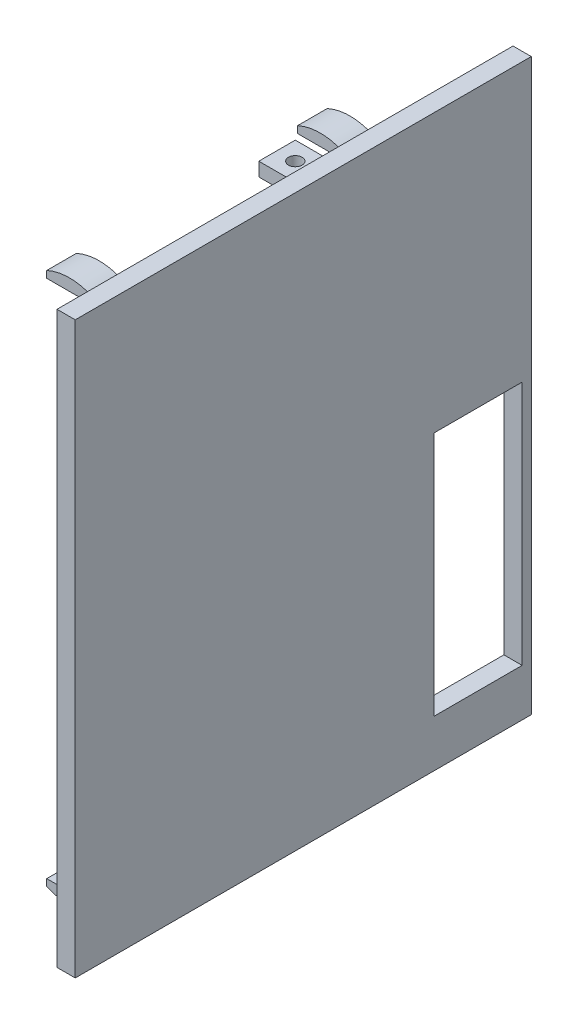
SolidWorks part; units mm, degrees
ref_plane "Front Plane" through (0, 0, 0) normal (0, 0, 1) x (1, 0, 0)
ref_plane "Top Plane" through (0, 0, 0) normal (0, 1, 0) x (1, 0, 0)
ref_plane "Right Plane" through (0, 0, 0) normal (1, 0, 0) x (0, 0, -1)
sketch "Sketch2" plane through (0, 0, 0) normal (0, 0, 1) x (1, 0, 0)
  line L1 (74.8705, 8.9597) -> (70.8705, 8.9597)
  line L2 (74.8705, 8.9597) -> (74.8705, -116.0403)
  line L3 (74.8705, -116.0403) -> (70.8705, -116.0403)
  line L4 (70.8705, 8.9597) -> (70.8705, -116.0403)
  dimension "D1" = 4
  dimension "D2" = 125
extrude "Boss-Extrude2" add sketch "Sketch2" along normal blind 100
sketch "Sketch6" plane through (70.8705, -52.3407, -13.6515) normal (-1, 0, 0) x (0, 1, 0)
  line L0 (61.3004, -13.6515) -> (-63.6996, -13.6515) construction
  line L1 (0.4704, -34.9991) -> (-53.3296, -34.9991)
  line L2 (0.4704, -34.9991) -> (0.4704, -15.6515)
  line L3 (0.4704, -15.6515) -> (-53.3296, -15.6515)
  line L4 (-53.3296, -34.9991) -> (-53.3296, -15.6515)
  line L6 (-63.6996, -113.6515) -> (-63.6996, -13.6515) construction
  dimension "D1" = 2
  dimension "D2" = 53.8
  dimension "D3" = 10.37
extrude "Cut-Extrude1" cut sketch "Sketch6" against normal up to next
sketch "Sketch7" plane through (74.8705, 0, 0) normal (1, 0, 0) x (0, 0, -1)
  line L0 (0, -116.0403) -> (0, 8.9597) construction
  line L1 (-50, -19.607) -> (-51.5, -19.607)
  line L2 (-50, -19.607) -> (-50, -39.607)
  line L3 (-50, -39.607) -> (-51.5, -39.607)
  line L4 (-51.5, -19.607) -> (-51.5, -39.607)
  dimension "D1" = 50
  dimension "D2" = 20
  dimension "D3" = 1.5
extrude "Boss-Extrude3" [suppressed] add sketch "Sketch7" against normal blind 16.5
pattern_linear "LPattern1" [suppressed] count 2 spacing 25
sketch "Sketch9" plane through (70.8705, 0, 0) normal (-1, 0, 0) x (0, 0, 1)
  line L0 (100, -116.0403) -> (0, -116.0403) construction
  line L1 (83.25, -110.5403) -> (89.75, -110.5403)
  line L2 (83.25, -110.5403) -> (83.25, -112.0403)
  line L3 (83.25, -112.0403) -> (89.75, -112.0403)
  line L4 (89.75, -110.5403) -> (89.75, -112.0403)
  line L5 (100, 8.9597) -> (100, -116.0403) construction
  dimension "D1" = 4
  dimension "D2" = 10.25
  dimension "D3" = 6.5
  dimension "D4" = 1.5
extrude "Boss-Extrude4" add sketch "Sketch9" along normal blind 12.5
sketch "Sketch10" plane through (0, 0, 89.75) normal (0, 0, 1) x (1, 0, 0)
  line L0 (58.3705, -112.0403) -> (70.8705, -112.0403) construction
  line L1 (58.3705, -112.0403) -> (68.3705, -112.0403)
  arc A0 (68.3705, -112.0403) -> (58.3705, -112.0403) centre (63.3705, -101.1316) cw
  dimension "D2" = 12
  dimension "D1" = 10
extrude "Boss-Extrude5" add sketch "Sketch10" against normal up to surface (6.5 mm away) up to face at (64.6205, -111.2903, 83.25)
pattern_linear "LPattern2" count 2 spacing 55 along (0, 0, -1) of "Boss-Extrude4", "Boss-Extrude5"
ref_plane "Plane2" through (0, -53.5403, 0) normal (0, 1, 0) x (1, 0, 0)
mirror "Mirror1" about plane through (0, -53.5403, 0) normal (0, 1, 0) of "LPattern2", "Boss-Extrude4", "Boss-Extrude5"
sketch "Sketch11" plane through (70.8705, 0, 0) normal (-1, 0, 0) x (0, 0, 1)
  line L0 (100, 8.9597) -> (100, -116.0403) construction
  line L1 (37.75, -109.0403) -> (45.75, -109.0403)
  line L2 (37.75, -109.0403) -> (37.75, -112.0403)
  line L3 (37.75, -112.0403) -> (45.75, -112.0403)
  line L4 (45.75, -109.0403) -> (45.75, -112.0403)
  line L5 (37.75, -109.0403) -> (45.75, -112.0403) construction
  line L6 (37.75, -112.0403) -> (45.75, -109.0403) construction
  line L7 (100, -116.0403) -> (0, -116.0403) construction
  point P0 (41.75, -110.5403)
  point P7 (37.75, -110.5403)
  dimension "D1" = 58.25
  dimension "D2" = 8
  dimension "D3" = 3
  dimension "D4" = 4
extrude "Boss-Extrude6" add sketch "Sketch11" along normal blind 10
sketch "Sketch12" plane through (0, -112.0403, 0) normal (0, -1, 0) x (-1, 0, 0)
  line L1 (-60.8705, -37.75) -> (-70.8705, -37.75) construction
  line L3 (-70.8705, -37.75) -> (-70.8705, -45.75) construction
  circle A0 centre (-64.8705, -41.75) radius 1.5
  point P4 (0, 0)
  point P6 (-70.8705, -43.0105)
  dimension "D1" = 3
  dimension "D2" = 4
  dimension "D3" = 6
extrude "Cut-Extrude2" cut sketch "Sketch12" along direction (0, -1, 0) on the side against the normal up to next (3 mm away)
mirror "Mirror2" about plane through (0, -53.5403, 0) normal (0, 1, 0) of "Cut-Extrude2", "Boss-Extrude6"
